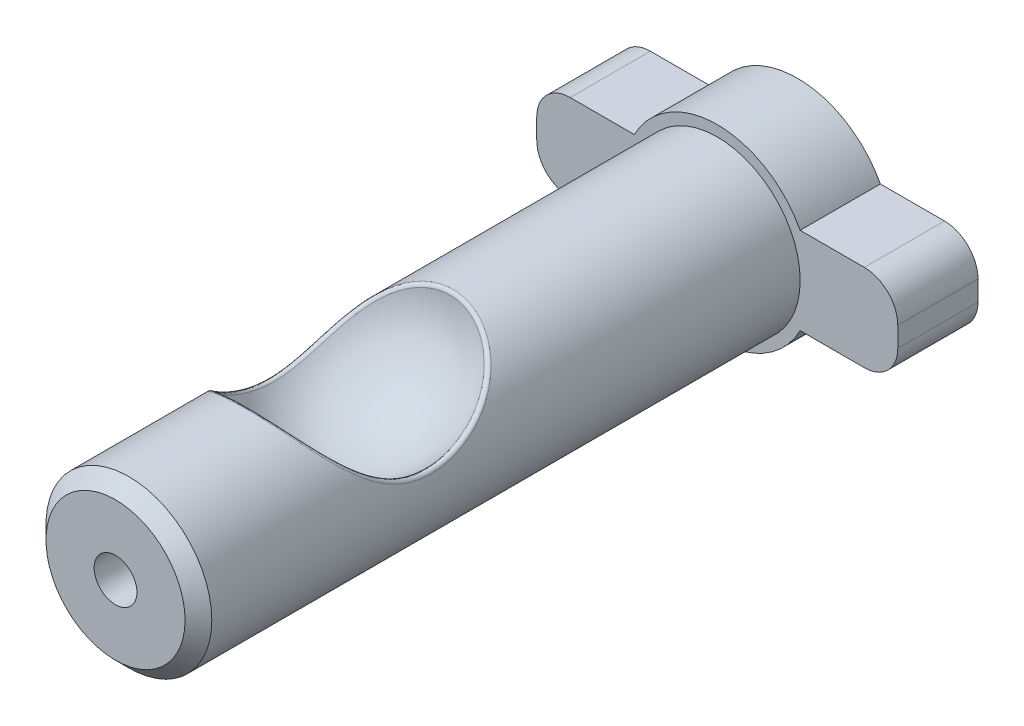
SolidWorks part; units mm, degrees
ref_plane "Plan de face" through (0, 0, 0) normal (0, 0, 1) x (1, 0, 0)
ref_plane "Plan de dessus" through (0, 0, 0) normal (0, 1, 0) x (1, 0, 0)
ref_plane "Plan de droite" through (0, 0, 0) normal (1, 0, 0) x (0, 0, -1)
sketch "Esquisse1" plane through (0, 0, 0) normal (0, 0, 1) x (1, 0, 0)
  line L0 (12.3996, 6.5) -> (22, 6.5)
  line L1 (-22, 6.5) -> (-12.3996, 6.5)
  line L2 (-27, 1.5) -> (-27, -1.5)
  line L3 (-22, -6.5) -> (-12.3996, -6.5)
  line L4 (27, 1.5) -> (27, -1.5)
  line L5 (12.3996, -6.5) -> (22, -6.5)
  arc A0 (-12.3996, -6.5) -> (12.3996, -6.5) centre (0, 0) ccw
  arc A5 (12.3996, 6.5) -> (-12.3996, 6.5) centre (0, 0) ccw
  arc A6 (-27, 1.5) -> (-22, 6.5) centre (-22, 1.5) cw
  arc A7 (22, -6.5) -> (27, -1.5) centre (22, -1.5) ccw
  arc A8 (27, 1.5) -> (22, 6.5) centre (22, 1.5) ccw
  arc A9 (-22, -6.5) -> (-27, -1.5) centre (-22, -1.5) cw
  dimension "D6" = 14
  dimension "D7" = 5
  dimension "D8" = 5
  dimension "D2" = 13
  dimension "D3" = 6.5
  dimension "D4" = 54
  dimension "D5" = 27
extrude "Boss.-Extru.1" add sketch "Esquisse1" along normal blind 12
sketch "Esquisse2" plane through (0, 0, 0) normal (0, 0, 1) x (1, 0, 0)
  circle A0 centre (0, 0) radius 12.4
  dimension "D1" = 24.8
extrude "Boss.-Extru.3" add sketch "Esquisse2" along normal blind 90 from surface at 12 starting at face at (0, 0, 12)
sketch "Esquisse12" plane through (0, 0, 0) normal (1, 0, 0) x (0, 0, -1)
  line L0 (-12, 12.4) -> (-102, 12.4) construction
  line L1 (-52, 12.4) -> (-82, 12.4)
  line L2 (-12, 14) -> (-12, 6.5) construction
  arc A0 (-82, 12.4) -> (-52, 12.4) centre (-67, 12.4) ccw
  dimension "D2" = 30
  dimension "D1" = 55
revolve "Enlèvement de matière-Révolution20" cut sketch "Esquisse12" angle 360 about L1
chamfer "Chanfrein2" distance 2 angle 45 1 edges at (12.4, 0, 102)
fillet "Congé1" radius 0.5 1 edges at (-11.935, 3.3639, 67.9518)
hole_wizard "Dégagement M61" positions "Esquisse3D1" profile "Esquisse15" hole size "M6" standard "ISO"
sketch3d "Esquisse3D1"
  line L0 (0, 0, 100) -> (0, 0, 102) construction
  point P0 (0, 0, 102)
sketch "Esquisse15" plane through (0, 0, 102) normal (1, 0, 0) x (0, -1, 0)
  line L0 (0, 0) -> (0, 13.9228)
  line L1 (0, 13.9228) -> (3.2, 12)
  line L2 (3.2, 12) -> (3.2, 0)
  line L5 (3.2, 0) -> (0, 0)
  line L10 (0, 13.9228) -> (-3.2, 12) construction
  line L11 (0, -6.35) -> (0, 107.95) construction
  dimension "Diamètre du perçage" = 6.4
  dimension "Profondeur du perçage" = 12
  dimension "Angle de pointe" = 118
